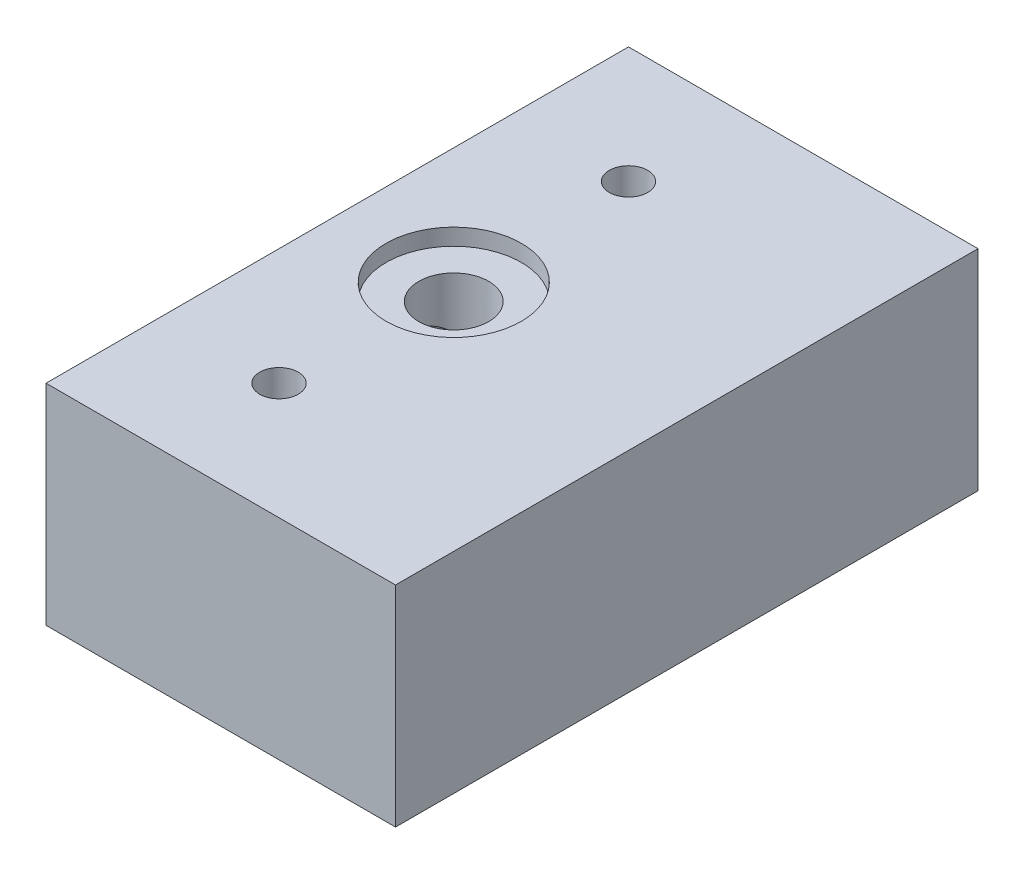
SolidWorks part; units mm, degrees
ref_plane "Front Plane" through (0, 0, 0) normal (0, 0, 1) x (1, 0, 0)
ref_plane "Top Plane" through (0, 0, 0) normal (0, 1, 0) x (1, 0, 0)
ref_plane "Right Plane" through (0, 0, 0) normal (1, 0, 0) x (0, 0, -1)
sketch "Sketch1" plane through (0, 0, 0) normal (1, 0, 0) x (0, 0, -1)
  line L1 (-25, 18) -> (25, 18)
  line L2 (-25, 18) -> (-25, 0)
  line L3 (-25, 0) -> (25, 0)
  line L4 (25, 18) -> (25, 0)
  point P4 (0, 0)
  dimension "D1" = 18
  dimension "D2" = 50
extrude "Boss-Extrude1" add sketch "Sketch1" along normal blind 30
sketch "Sketch2" plane through (0, 0, 0) normal (-1, 0, 0) x (0, 0, 1)
  line L0 (0, 0) -> (0, 10) construction
  line L1 (25, 0) -> (-25, 0) construction
  line L2 (-10, 0) -> (-10, 10) construction
  point P5 (0, 10)
  point P8 (-10, 10)
  dimension "D1" = 10
  dimension "D2" = 10
  dimension "D3" = 10
hole_wizard "Ø6.0 (6) Diameter Hole1" positions "3DSketch1" profile "Sketch3" hole size "Ø6.0" standard "BSI"
sketch3d "3DSketch1"
  point P0 (0, 10, 0)
sketch "Sketch3" plane through (0, 10, 0) normal (0, 1, 0) x (0, 0, 1)
  line L0 (0, 0) -> (0, 13.8026)
  line L1 (0, 13.8026) -> (3, 12)
  line L2 (3, 12) -> (3, 0)
  line L5 (3, 0) -> (0, 0)
  line L10 (0, 13.8026) -> (-3, 12) construction
  line L11 (0, -6.35) -> (0, 107.95) construction
  dimension "Hole Dia." = 6
  dimension "Hole Depth" = 12
  dimension "Drill Angle" = 118
hole_wizard "M3x0.5 Tapped Hole1" positions "3DSketch2" profile "Sketch4" tap size "M3x0.5" standard "BSI"
sketch3d "3DSketch2"
  point P0 (0, 10, -10)
sketch "Sketch4" plane through (0, 10, -10) normal (0, 1, 0) x (0, 0, 1)
  line L0 (0, 0) -> (0, 12.2511)
  line L1 (0, 12.2511) -> (1.25, 11.5)
  line L2 (1.25, 11.5) -> (1.25, 0)
  line L5 (1.25, 0) -> (0, 0)
  line L10 (0, 12.2511) -> (-1.25, 11.5) construction
  line L11 (0, -6.35) -> (0, 107.95) construction
  dimension "Tap Drill Dia." = 2.5
  dimension "Tap Drill Depth" = 11.5
  dimension "Drill Angle" = 118
cosmetic thread "Hole Thread1" parameters "D1"=10, "D2"=3
mirror "Mirror1" about plane through (0, 0, 0) normal (0, 0, 1) of "M3x0.5 Tapped Hole1"
sketch "Sketch5" plane through (0, 18, 0) normal (0, 1, 0) x (1, 0, 0)
  line L0 (0, 0) -> (30, 0) construction
  line L1 (0, 25) -> (0, -25) construction
  line L2 (30, 25) -> (30, -25) construction
  circle A1 centre (10, 0) radius 5.805
  point P4 (10, 0)
  dimension "D3" = 11.61
  dimension "D1" = 10
hole_wizard "Ø6.0 (6) Diameter Hole2" positions "3DSketch3" profile "Sketch7" hole size "Ø6.0" standard "BSI"
sketch3d "3DSketch3"
  line L0 (0, 18, 0) -> (30, 18, 0) construction
  line L1 (0, 18, -25) -> (0, 18, 25) construction
  line L2 (30, 18, -25) -> (30, 18, 25) construction
  point P12 (10, 18, 0)
  point P13 (10, 18, 0)
  point P17 (0, 0, 0)
  dimension "D1" = 10
sketch "Sketch7" plane through (10, 18, 0) normal (1, 0, 0) x (0, 0, 1)
  line L0 (0, 0) -> (0, 9.8026)
  line L1 (0, 9.8026) -> (3, 8)
  line L2 (3, 8) -> (3, 0)
  line L5 (3, 0) -> (0, 0)
  line L10 (0, 9.8026) -> (-3, 8) construction
  line L11 (0, -6.35) -> (0, 107.95) construction
  dimension "Hole Dia." = 6
  dimension "Hole Depth" = 8
  dimension "Drill Angle" = 118
extrude "Cut-Extrude1" cut sketch "Sketch5" against normal blind 1.424
sketch "Sketch8" plane through (0, 18, 0) normal (0, 1, 0) x (1, 0, 0)
  line L0 (0, 0) -> (10, 0) construction
  line L2 (10, 0) -> (10, 15) construction
  point P6 (10, 15)
  dimension "D1" = 15
hole_wizard "M4x0.7 Tapped Hole1" positions "3DSketch4" profile "Sketch9" tap size "M4x0.7" standard "BSI"
sketch3d "3DSketch4"
  point P0 (10, 18, -15)
sketch "Sketch9" plane through (10, 18, -15) normal (1, 0, 0) x (0, 0, 1)
  line L0 (0, 0) -> (0, 15.0914)
  line L1 (0, 15.0914) -> (1.65, 14.1)
  line L2 (1.65, 14.1) -> (1.65, 0)
  line L5 (1.65, 0) -> (0, 0)
  line L10 (0, 15.0914) -> (-1.65, 14.1) construction
  line L11 (0, -6.35) -> (0, 107.95) construction
  dimension "Tap Drill Dia." = 3.3
  dimension "Tap Drill Depth" = 14.1
  dimension "Drill Angle" = 118
cosmetic thread "Hole Thread2" parameters "D1"=12, "D2"=4
mirror "Mirror2" about plane through (0, 0, 0) normal (0, 0, 1) of "M4x0.7 Tapped Hole1"
